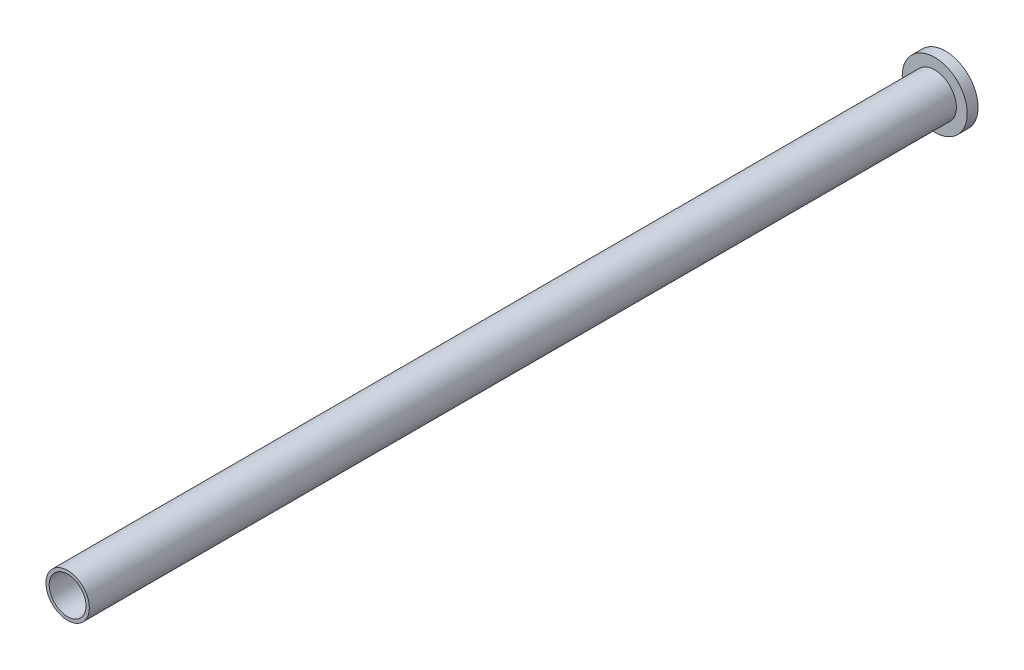
SolidWorks part; units mm, degrees
ref_plane "Front Plane" through (0, 0, 0) normal (0, 0, 1) x (1, 0, 0)
ref_plane "Top Plane" through (0, 0, 0) normal (0, 1, 0) x (1, 0, 0)
ref_plane "Right Plane" through (0, 0, 0) normal (1, 0, 0) x (0, 0, -1)
sketch "Sketch1" plane through (0, 0, 0) normal (0, 0, 1) x (1, 0, 0)
  line L0 (17, 0) -> (20, 0) construction
  circle A0 centre (0, 0) radius 20 construction
  circle A1 centre (0, 0) radius 17 construction
  dimension "ID" = 34
  dimension "OD" = 40
  dimension "Wall Thickness" = 3
sketch "Sketch2" plane through (0, 0, 0) normal (1, 0, 0) x (0, 0, -1)
  line L0 (-400, 0) -> (400, 0) construction
  line L1 (-357.5, 20) -> (-357.5, -20) construction
  line L2 (357.5, 20) -> (357.5, -20) construction
  point P4 (0, 0)
  point P8 (-357.5, 0)
  point P11 (357.5, 0)
  dimension "Length" = 800
  dimension "D1" = 42.5
  dimension "D2" = 42.5
  dimension "D3" = 40
sketch "Sketch3" plane through (0, 0, 0) normal (0, 0, 1) x (1, 0, 0)
  circle A0 centre (0, 0) radius 20
  circle A1 centre (0, 0) radius 20 construction
  circle A2 centre (0, 0) radius 17 construction
  circle A3 centre (0, 0) radius 17
extrude "Boss-Extrude1" add sketch "Sketch3" along normal up to vertex (400 mm away) and the other way up to vertex (400 mm away) up to point (0, 0, 400) other way up to point (0, 0, -400)
sketch "Sketch7" plane through (0, 0, -400) normal (0, 0, -1) x (-1, 0, 0)
  circle A1 centre (0, 0) radius 30
  dimension "D1" = 60
extrude "Boss-Extrude4" add sketch "Sketch7" along normal blind 10
equation "\"D1@Sketch2\"=\"ID@Sketch1\"*1.25"
equation "\"D2@Sketch2\"=\"D1@Sketch2\""
equation "\"D3@Sketch2\"= \"OD@Sketch1\""
